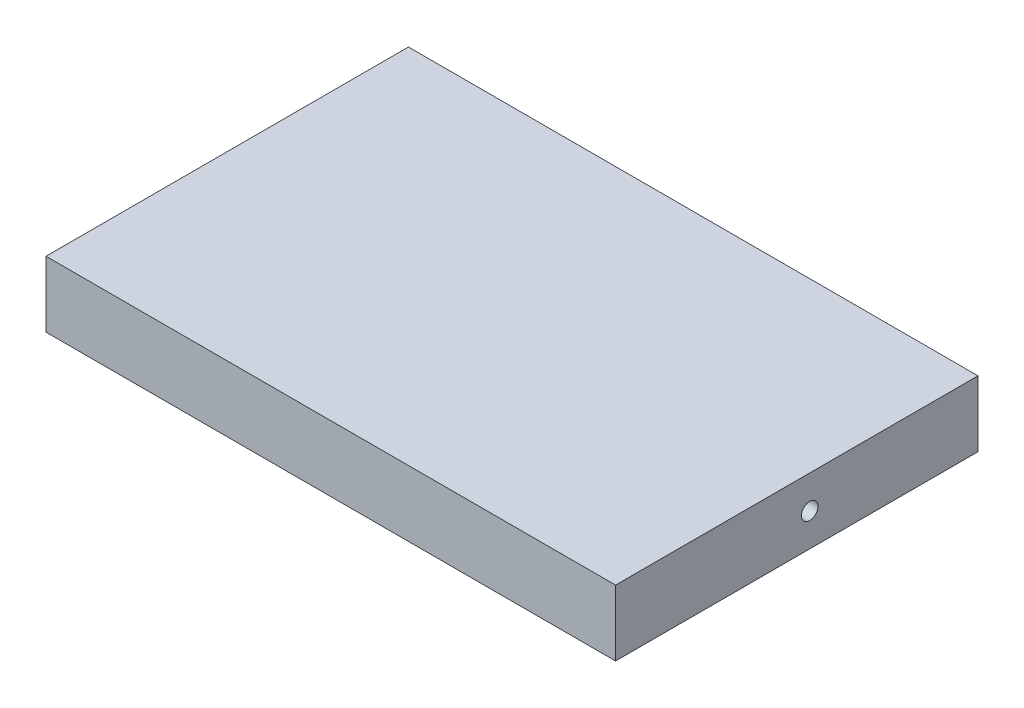
SolidWorks part; units mm, degrees
ref_plane "Front Plane" through (0, 0, 0) normal (0, 0, 1) x (1, 0, 0)
ref_plane "Top Plane" through (0, 0, 0) normal (0, 1, 0) x (1, 0, 0)
ref_plane "Right Plane" through (0, 0, 0) normal (1, 0, 0) x (0, 0, -1)
sketch "Sketch1" plane through (0, 0, 0) normal (0, 1, 0) x (1, 0, 0)
  line L1 (-110, 70) -> (110, 70)
  line L2 (-110, 70) -> (-110, -70)
  line L3 (-110, -70) -> (110, -70)
  line L4 (110, 70) -> (110, -70)
  point P0 (0, 0)
extrude "Boss-Extrude1" add sketch "Sketch1" along normal blind 25.4
sketch "Sketch2" plane through (110, 0, 0) normal (1, 0, 0) x (0, 0, -1)
  circle A0 centre (5, 12.7) radius 3.2
sketch "Sketch3" plane through (-110, 0, 0) normal (-1, 0, 0) x (0, 0, 1)
  circle A0 centre (-5, 12.7) radius 3.2
extrude "Cut-Extrude1" cut sketch "Sketch3" against normal blind 20
extrude "Cut-Extrude2" cut sketch "Sketch2" against normal blind 20 contours A0
